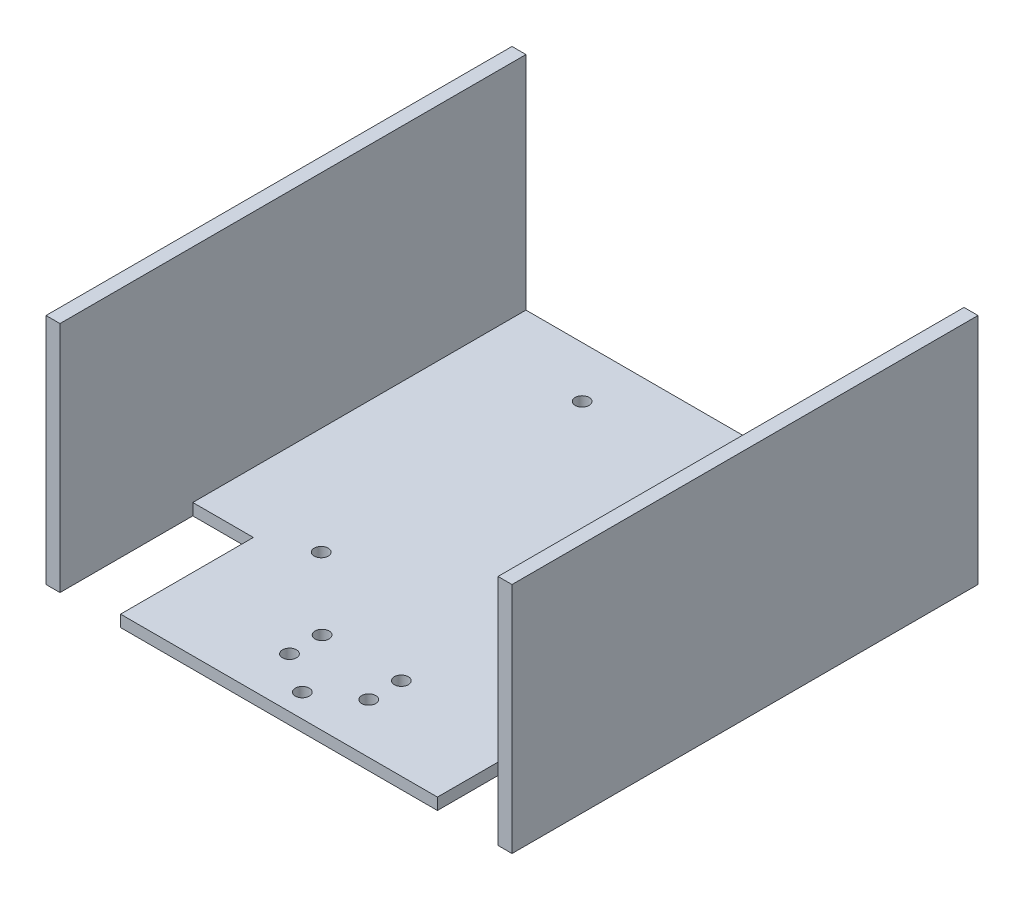
SolidWorks part; units mm, degrees
ref_plane "Alzado" through (0, 0, 0) normal (0, 0, 1) x (1, 0, 0)
ref_plane "Planta" through (0, 0, 0) normal (0, 1, 0) x (1, 0, 0)
ref_plane "Vista lateral" through (0, 0, 0) normal (1, 0, 0) x (0, 0, -1)
sketch "Croquis1" plane through (0, 0, 0) normal (0, 0, 1) x (1, 0, 0)
  line L0 (50, 0) -> (-50, 0)
  line L1 (-50, 0) -> (-50, 50)
  line L2 (-50, 50) -> (-47, 50)
  line L3 (-47, 50) -> (-47, 2.5)
  line L4 (-47, 2.5) -> (47, 2.5)
  line L5 (0, 2.5) -> (0, 0)
  line L6 (0, 0) -> (0, 13.9963) construction
  line L7 (47, 50) -> (47, 2.5)
  line L8 (50, 50) -> (47, 50)
  line L9 (50, 0) -> (50, 50)
  dimension "D1" = 50
  dimension "D2" = 50
  dimension "D3" = 3
  dimension "D4" = 2.5
extrude "Saliente-Extruir1" add sketch "Croquis1" against normal blind 100 contours L4 L7 L8 L9 L0 L1 L2 L3
sketch "Croquis2" plane through (0, 2.5, 0) normal (0, 1, 0) x (1, 0, 0)
  line L0 (0, 0) -> (0, 100) construction
  line L1 (-47, 0) -> (-34, 0)
  line L2 (-47, 0) -> (-47, 28.5)
  line L3 (-47, 28.5) -> (-34, 28.5)
  line L4 (-34, 0) -> (-34, 28.5)
  line L5 (-47, 100) -> (47, 100) construction
  line L6 (47, 28.5) -> (34, 28.5)
  line L7 (34, 0) -> (34, 28.5)
  line L8 (47, 0) -> (34, 0)
  line L9 (47, 0) -> (47, 28.5)
  dimension "D1" = 13
  dimension "D2" = 28.5
extrude "Cortar-Extruir2" cut sketch "Croquis2" against normal blind 10
ref_plane "Plano1" through (0, 2.5, 0) normal (0, 1, 0) x (1, 0, 0)
sketch "Croquis3" plane through (0, 2.5, 0) normal (0, 1, 0) x (1, 0, 0)
  line L0 (0, 0) -> (0, 100) construction
  line L1 (-47, 100) -> (47, 100) construction
  line L2 (-34, 0) -> (34, 0) construction
  circle A1 centre (0, 5) radius 1.5
  dimension "D1" = 3
  dimension "D2" = 5
extrude "Cortar-Extruir3" cut sketch "Croquis3" against normal blind 5
sketch "Croquis4" plane through (0, 2.5, 0) normal (0, 1, 0) x (1, 0, 0)
  line L0 (0, 0) -> (0, 100) construction
  line L1 (-47, 100) -> (47, 100) construction
  line L2 (0, 17.75) -> (-8.5, 17.75) construction
  line L3 (0, 10.75) -> (-8.5, 10.75) construction
  line L4 (-34, 14.25) -> (0, 14.25) construction
  line L6 (-34, 0) -> (-34, 28.5) construction
  circle A0 centre (-8.5, 17.75) radius 1.5
  circle A1 centre (-8.5, 10.75) radius 1.5
  circle A2 centre (8.5, 10.75) radius 1.5
  circle A3 centre (8.5, 17.75) radius 1.5
  dimension "D3" = 3
  dimension "D1" = 8.5
  dimension "D2" = 3.5
  dimension "D4" = 3.5
extrude "Cortar-Extruir4" cut sketch "Croquis4" against normal blind 10
sketch "Croquis5" plane through (0, 2.5, 0) normal (0, 1, 0) x (1, 0, 0)
  line L0 (-24, 100) -> (-24, 89.05) construction
  line L1 (-47, 100) -> (47, 100) construction
  line L2 (-47, 100) -> (-47, 0) construction
  line L3 (0, 100) -> (0, 0) construction
  circle A0 centre (-24, 89.05) radius 1.5
  circle A1 centre (-24, 33.05) radius 1.5
  circle A2 centre (24, 33.05) radius 1.5
  circle A3 centre (24, 89.05) radius 1.5
  dimension "D3" = 3
  dimension "D1" = 10.95
  dimension "D2" = 23
  dimension "D4" = 56
extrude "Cortar-Extruir6" cut sketch "Croquis5" against normal blind 10
